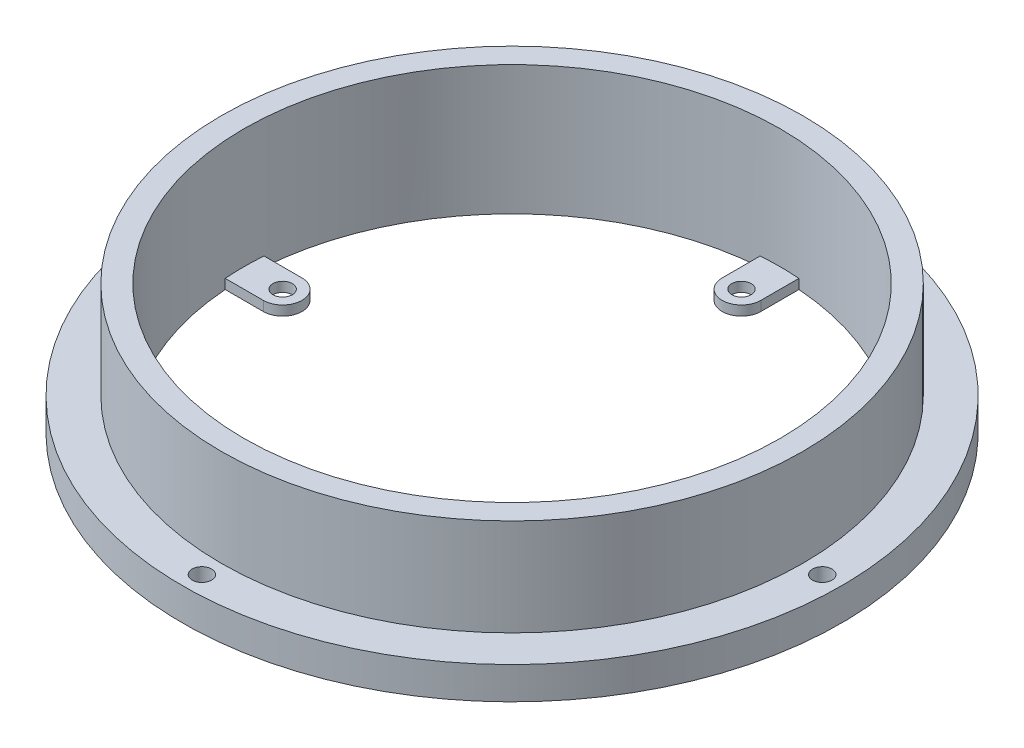
SolidWorks part; units mm, degrees
ref_plane "Front Plane" through (0, 0, 0) normal (0, 0, 1) x (1, 0, 0)
ref_plane "Top Plane" through (0, 0, 0) normal (0, 1, 0) x (1, 0, 0)
ref_plane "Right Plane" through (0, 0, 0) normal (1, 0, 0) x (0, 0, -1)
sketch "Sketch1" plane through (0, 0, 0) normal (0, 1, 0) x (1, 0, 0)
  circle A0 centre (0, 0) radius 42
  circle A1 centre (0, 0) radius 45
  dimension "D1" = 3
extrude "Boss-Extrude1" add sketch "Sketch1" along normal blind 20
sketch "Sketch2" plane through (0, 0, 0) normal (0, -1, 0) x (1, 0, 0)
  line L0 (45, 0) -> (48, 0)
  circle A1 centre (0, 0) radius 42 construction
  circle A2 centre (0, 0) radius 42
  circle A3 centre (0, 0) radius 45 construction
  circle A4 centre (0, 0) radius 45
  circle A5 centre (48, 0) radius 1.5
  circle A6 centre (0, 0) radius 51
  circle A7 centre (0, -48) radius 1.5
  circle A8 centre (-48, 0) radius 1.5
  circle A9 centre (0, 48) radius 1.5
  point P22 (0, 0)
  dimension "D1" = 3
  dimension "D2" = 6
  dimension "D3" = 4
extrude "Boss-Extrude2" add sketch "Sketch2" against normal blind 5
sketch "Sketch3" plane through (0, 20, 0) normal (0, 1, 0) x (1, 0, 0)
  circle A1 centre (0, 0) radius 42 construction
  circle A2 centre (0, 0) radius 41.5
  circle A3 centre (0, 0) radius 41.5
  circle A4 centre (0, 0) radius 42
  dimension "D1" = 0.5
extrude "Boss-Extrude3" add sketch "Sketch3" against normal up to surface (20 mm away) up to face at (0, 0, 42)
sketch "Sketch5" plane through (0, 0, 0) normal (0, -1, 0) x (1, 0, 0)
  line L0 (35.5, 3) -> (42.1944, 3)
  line L2 (-3, 35.5) -> (-3, 42.1944)
  line L3 (-3, 42.1944) -> (3, 42.1944)
  line L4 (3, 35.5) -> (3, 42.1944)
  line L5 (42.1944, 3) -> (42.1944, -3)
  line L6 (35.5, -3) -> (42.1944, -3)
  line L7 (3, -35.5) -> (3, -42.1944)
  line L8 (3, -42.1944) -> (-3, -42.1944)
  line L9 (-3, -35.5) -> (-3, -42.1944)
  line L10 (-35.5, -3) -> (-42.1944, -3)
  line L11 (-42.1944, -3) -> (-42.1944, 3)
  line L12 (-35.5, 3) -> (-42.1944, 3)
  circle A0 centre (35.5, 0) radius 1.5
  circle A1 centre (0, 35.5) radius 1.5
  arc A2 (-3, 35.5) -> (3, 35.5) centre (0, 35.5) ccw
  circle A4 centre (0, 35.5) radius 3 construction
  arc A5 (35.5, 3) -> (35.5, -3) centre (35.5, 0) ccw
  circle A6 centre (0, -35.5) radius 1.5
  arc A7 (3, -35.5) -> (-3, -35.5) centre (0, -35.5) ccw
  circle A8 centre (-35.5, 0) radius 1.5
  arc A9 (-35.5, -3) -> (-35.5, 3) centre (-35.5, 0) ccw
  point P7 (2.8689, 36.3771)
  point P36 (0, 0)
  dimension "D1" = 4
extrude "Boss-Extrude4" add sketch "Sketch5" against normal blind 1.5
